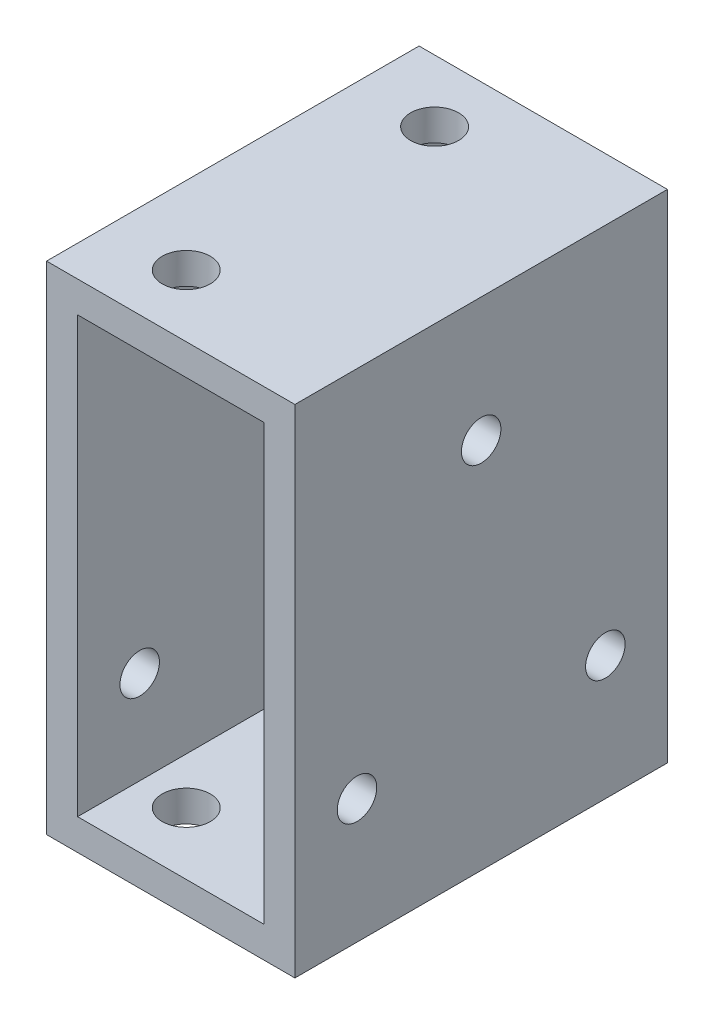
SolidWorks part; units mm, degrees
ref_plane "Front Plane" through (0, 0, 0) normal (0, 0, 1) x (1, 0, 0)
ref_plane "Top Plane" through (0, 0, 0) normal (0, 1, 0) x (1, 0, 0)
ref_plane "Right Plane" through (0, 0, 0) normal (1, 0, 0) x (0, 0, -1)
sketch "Sketch1" plane through (0, 0, 0) normal (0, 0, 1) x (1, 0, 0)
  line L0 (-9.525, 22.225) -> (9.525, 22.225)
  line L1 (-12.7, 25.4) -> (12.7, 25.4)
  line L2 (-12.7, 25.4) -> (-12.7, -25.4)
  line L3 (-12.7, -25.4) -> (12.7, -25.4)
  line L4 (12.7, 25.4) -> (12.7, -25.4)
  line L5 (-12.7, 25.4) -> (12.7, -25.4) construction
  line L6 (-12.7, -25.4) -> (12.7, 25.4) construction
  line L7 (9.525, 22.225) -> (9.525, -22.225)
  line L8 (-9.525, -22.225) -> (9.525, -22.225)
  line L9 (-9.525, 22.225) -> (-9.525, -22.225)
  point P0 (0, 0)
  dimension "D1" = 25.4
  dimension "D2" = 50.8
  dimension "D3" = 3.175
extrude "Boss-Extrude1" add sketch "Sketch1" along normal mid plane 38.1
hole_wizard "#10 (0.1935) Diameter Hole1" positions "Sketch3" profile "Sketch2" hole size "#10" standard "ANSI Inch" end condition through all
sketch "Sketch3" plane through (0, 25.4, 0) normal (0, 1, 0) x (1, 0, 0)
  line L0 (12.7, -19.05) -> (-12.7, -19.05) construction
  line L1 (-4.7625, 12.7) -> (-4.7625, -12.7) construction
  line L2 (-12.7, -19.05) -> (-12.7, 19.05) construction
  point P0 (-4.7625, -12.7)
  point P2 (-4.7625, 12.7)
  dimension "D1" = 25.4
  dimension "D2" = 6.35
  dimension "D3" = 7.9375
sketch "Sketch2" plane through (-4.7625, 25.4, 12.7) normal (1, 0, 0) x (0, 0, 1)
  line L0 (0, 0) -> (0, 50.8)
  line L1 (0, 50.8) -> (2.4574, 50.8)
  line L2 (2.4574, 50.8) -> (2.4574, 0)
  line L5 (2.4574, 0) -> (0, 0)
  line L11 (0, -6.35) -> (0, 107.95) construction
  dimension "Thru Hole Dia." = 4.9149
  dimension "Thru Hole Depth" = 50.8
hole_wizard "#10-32 Tapped Hole1" positions "Sketch5" profile "Sketch4" tap size "#10-32" standard "ANSI Inch" end condition through all
sketch "Sketch5" plane through (-12.7, 0, 0) normal (-1, 0, 0) x (0, 0, 1)
  line L0 (-19.05, 25.4) -> (-19.05, -25.4) construction
  line L1 (-12.7, -12.7) -> (12.7, -12.7) construction
  line L3 (19.05, 25.4) -> (-19.05, 25.4) construction
  line L4 (19.05, -25.4) -> (-19.05, -25.4) construction
  point P0 (-12.7, -12.7)
  point P2 (12.7, -12.7)
  point P4 (0, 12.7)
  dimension "D1" = 19.05
  dimension "D2" = 6.35
  dimension "D3" = 25.4
  dimension "D4" = 12.7
  dimension "D5" = 12.7
sketch "Sketch4" plane through (-12.7, -12.7, -12.7) normal (0, 1, 0) x (0, 0, 1)
  line L0 (0, 0) -> (0, 25.4)
  line L1 (0, 25.4) -> (2.0193, 25.4)
  line L2 (2.0193, 25.4) -> (2.0193, 0)
  line L5 (2.0193, 0) -> (0, 0)
  line L11 (0, -6.35) -> (0, 107.95) construction
  dimension "Thread Major Dia." = 4.0386
  dimension "Thru Tap Drill Depth" = 25.4
